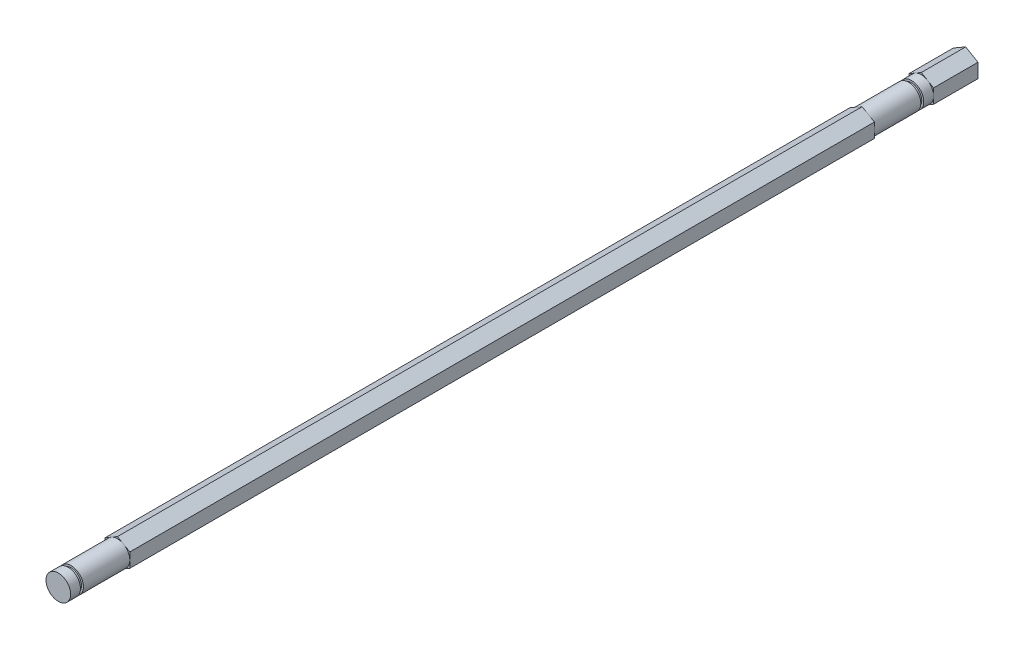
SolidWorks part; units mm, degrees
ref_plane "Front" through (0, 0, 0) normal (0, 0, 1) x (1, 0, 0)
ref_plane "Top" through (0, 0, 0) normal (0, 1, 0) x (1, 0, 0)
ref_plane "Right" through (0, 0, 0) normal (1, 0, 0) x (0, 0, -1)
sketch "Sketch1" plane through (0, 0, 0) normal (0, 0, 1) x (1, 0, 0)
  line L1 (0, 3.6662) -> (-3.175, 1.8331)
  line L2 (-3.175, 1.8331) -> (-3.175, -1.8331)
  line L3 (-3.175, -1.8331) -> (0, -3.6662)
  line L4 (0, -3.6662) -> (3.175, -1.8331)
  line L5 (3.175, -1.8331) -> (3.175, 1.8331)
  line L6 (3.175, 1.8331) -> (0, 3.6662)
  circle A0 centre (0, 0) radius 3.175 construction
  dimension "Width" = 6.35
sketch "Sketch2" plane through (0, 0, 0) normal (1, 0, 0) x (0, 0, -1)
  line L0 (-111.125, 0) -> (111.125, 0) construction
  line L1 (-60.325, 3.6662) -> (-60.325, -3.6662) construction
  line L2 (60.325, 3.6662) -> (60.325, -3.6662) construction
  line L3 (-111.125, 3.6662) -> (-111.125, -3.6662) construction
  line L4 (111.125, 3.6662) -> (111.125, -3.6662) construction
  point P2 (-60.325, 0)
  point P4 (60.325, 0)
  dimension "D1" = 50.8
  dimension "Length" = 222.25
  dimension "D2" = 50.8
sketch "Sketch3" plane through (0, 0, 0) normal (0, 0, 1) x (1, 0, 0)
  line L0 (0, 3.6662) -> (-3.175, 1.8331) construction
  line L1 (-3.175, 1.8331) -> (-3.175, -1.8331) construction
  line L2 (-3.175, -1.8331) -> (0, -3.6662) construction
  line L3 (0, -3.6662) -> (3.175, -1.8331) construction
  line L4 (3.175, -1.8331) -> (3.175, 1.8331) construction
  line L5 (3.175, 1.8331) -> (0, 3.6662) construction
  line L6 (0, 3.6662) -> (-3.175, 1.8331)
  line L7 (-3.175, 1.8331) -> (-3.175, -1.8331)
  line L8 (-3.175, -1.8331) -> (0, -3.6662)
  line L9 (0, -3.6662) -> (3.175, -1.8331)
  line L10 (3.175, -1.8331) -> (3.175, 1.8331)
  line L11 (3.175, 1.8331) -> (0, 3.6662)
extrude "Boss-Extrude2" add sketch "Sketch3" along normal up to vertex (111.125 mm away) and the other way up to vertex (111.125 mm away) up to point (0, 0, 111.125) other way up to point (0, 0, -111.125)
sketch "Sketch4" plane through (0, 0, 111.125) normal (0, 0, 1) x (1, 0, 0)
  circle A0 centre (0, 0) radius 3.175
  dimension "D1" = 6.35
extrude "Cut-Extrude1" cut sketch "Sketch4" against normal blind 15.24 flip side to cut
sketch "Sketch5" plane through (0, 0, -111.125) normal (0, 0, -1) x (-1, 0, 0)
  circle A0 centre (0, 0) radius 3.175
  dimension "D1" = 6.35
extrude "Cut-Extrude4" cut sketch "Sketch5" against normal blind 15.24 flip side to cut
ref_plane "Plane1" through (0, 0, -107.823) normal (0, 0, -1) x (-1, 0, 0)
sketch "Sketch7" plane through (0, 0, -107.823) normal (0, 0, -1) x (-1, 0, 0)
  circle A0 centre (0, 0) radius 2.667
  circle A1 centre (0, 0) radius 3.175
  circle A2 centre (0, 0) radius 3.175 construction
  dimension "D2" = 5.334
  dimension "D1" = 0
extrude "Cut-Extrude8" cut sketch "Sketch7" along normal blind 0.762 flip side to cut
ref_plane "Plane2" through (0, 0, 107.823) normal (0, 0, 1) x (1, 0, 0)
sketch "Sketch8" plane through (0, 0, 107.823) normal (0, 0, 1) x (1, 0, 0)
  circle A0 centre (0, 0) radius 2.667
  circle A1 centre (0, 0) radius 3.175
  circle A2 centre (0, 0) radius 3.175 construction
  dimension "D2" = 5.334
  dimension "D1" = 0
extrude "Cut-Extrude9" cut sketch "Sketch8" along normal blind 0.762 flip side to cut
sketch "Sketch11" plane through (0, 0, 111.125) normal (0, 0, 1) x (1, 0, 0)
  line L1 (0, 3.6662) -> (-3.175, 1.8331)
  line L2 (-3.175, 1.8331) -> (-3.175, -1.8331)
  line L3 (-3.175, -1.8331) -> (0, -3.6662)
  line L4 (0, -3.6662) -> (3.175, -1.8331)
  line L5 (3.175, -1.8331) -> (3.175, 1.8331)
  line L6 (3.175, 1.8331) -> (0, 3.6662)
  circle A0 centre (0, 0) radius 3.175 construction
  dimension "D1" = 3.6662
sketch "Sketch13" plane through (0, 0, -111.125) normal (0, 0, -1) x (-1, 0, 0)
  line L1 (0, 3.6662) -> (-3.175, 1.8331)
  line L2 (-3.175, 1.8331) -> (-3.175, -1.8331)
  line L3 (-3.175, -1.8331) -> (0, -3.6662)
  line L4 (0, -3.6662) -> (3.175, -1.8331)
  line L5 (3.175, -1.8331) -> (3.175, 1.8331)
  line L6 (3.175, 1.8331) -> (0, 3.6662)
  circle A0 centre (0, 0) radius 3.175 construction
  dimension "D1" = 3.6662
extrude "Boss-Extrude4" add sketch "Sketch13" along normal blind 11.43
